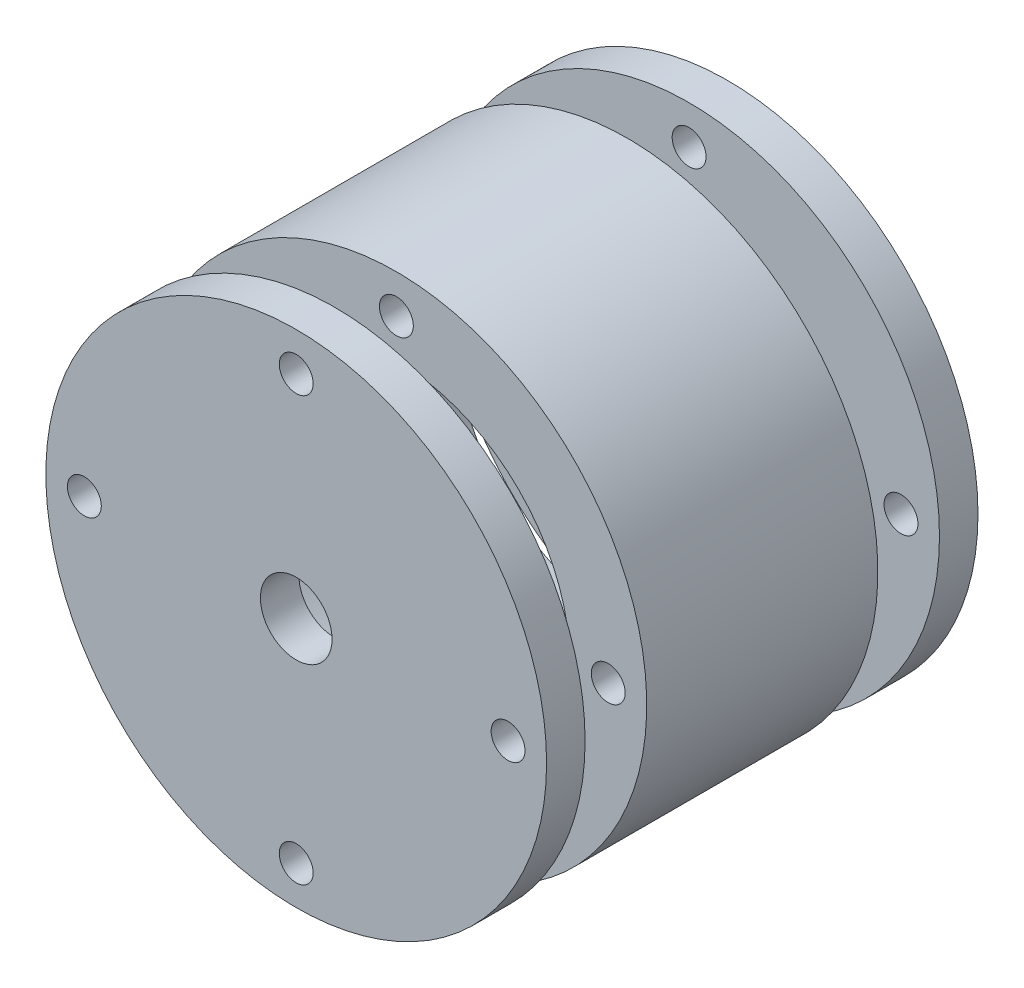
SolidWorks part; units mm, degrees
ref_plane "Front Plane" through (0, 0, 0) normal (0, 0, 1) x (1, 0, 0)
ref_plane "Top Plane" through (0, 0, 0) normal (0, 1, 0) x (1, 0, 0)
ref_plane "Right Plane" through (0, 0, 0) normal (1, 0, 0) x (0, 0, -1)
sketch "Sketch1" plane through (0, 0, 0) normal (0, 0, 1) x (1, 0, 0)
  line L0 (-32.9906, -34.2) -> (98.1862, -34.2)
  circle A0 centre (-32.9906, -34.2) radius 6.575 construction
  circle A1 centre (-32.9906, -34.2) radius 6.575
  circle A2 centre (-32.9906, -34.2) radius 8.875 construction
  circle A3 centre (-32.9906, -34.2) radius 8.875
sketch "Sketch2" plane through (0, 0, 0) normal (0, 0, 1) x (1, 0, 0)
  line L2 (-58.7906, -34.2) -> (-88.2906, -34.2)
  line L3 (-88.2906, -85) -> (-88.2906, 85) construction
  line L4 (88.2906, -34.2) -> (65.9936, -34.2)
  line L5 (-32.9906, -34.2) -> (98.1862, -34.2) construction
  line L6 (88.2906, 85) -> (88.2906, -85) construction
  circle A1 centre (33.4966, -33.7548) radius 4.65 construction
  circle A2 centre (33.4966, -33.7548) radius 4.65
  circle A3 centre (33.4966, -33.7548) radius 32.5
  circle A5 centre (33.4966, -33.7548) radius 27.5
  circle A6 centre (33.4966, -6.2548) radius 2.2
  circle A7 centre (5.9966, -33.7548) radius 2.2
  circle A8 centre (33.4966, -61.2548) radius 2.2
  circle A9 centre (60.9966, -33.7548) radius 2.2
  circle M40 centre (33.4966, -33.7548) radius 20.6
  circle M41 centre (33.4966, -6.2548) radius 2.2
  circle M42 centre (60.9966, -33.7548) radius 2.2
  circle M43 centre (33.4966, -61.2548) radius 2.2
  circle M44 centre (5.9966, -33.7548) radius 2.2
  dimension "D2" = 55
  dimension "D4" = 4.4
  dimension "D3" = 65
  dimension "D1" = 29.5
extrude "Boss-Extrude1" add sketch "Sketch2" along normal blind 5 contours A3 A2 | A3 A9 A5 A8 A7 A6 | A5 M42 M41 M44 M43 M40
sketch "Sketch3" plane through (0, 0, 0) normal (0, 0, -1) x (-1, 0, 0)
  line L0 (-5.9966, -33.7548) -> (-0.9966, -33.7548)
  line L1 (-5.9966, -33.7548) -> (-10.9966, -33.7548)
  circle A0 centre (-33.4966, -33.7548) radius 22.5
  circle A1 centre (-33.4966, -33.7548) radius 32.5
  circle A3 centre (-33.4966, -6.2548) radius 2.2
  circle A5 centre (-5.9966, -33.7548) radius 2.2
  circle A7 centre (-33.4966, -61.2548) radius 2.2
  circle A9 centre (-60.9966, -33.7548) radius 2.2
  circle A17 centre (-33.4966, -33.7548) radius 32.5
  circle A18 centre (-33.4966, -6.2548) radius 2.2
  circle A19 centre (-5.9966, -33.7548) radius 2.2
  circle A20 centre (-33.4966, -61.2548) radius 2.2
  circle A21 centre (-60.9966, -33.7548) radius 2.2
  dimension "D1" = 0
  dimension "D2" = 0
  dimension "D3" = 0
  dimension "D4" = 0
  dimension "D5" = 0
extrude "Boss-Extrude2" add sketch "Sketch3" along normal blind 30 from offset 8 separate body
ref_plane "Plane1" through (0, 0, -23) normal (0, 0, -1) x (-1, 0, 0)
mirror "Mirror1" about plane through (0, 0, -23) normal (0, 0, -1) of bodies 101
sketch "Sketch4" plane through (0, 0, 0) normal (0, 0, -1) x (-1, 0, 0)
  circle A0 centre (-33.4966, -33.7548) radius 4.65 construction
  circle A1 centre (-33.4966, -33.7548) radius 4.65
  circle A2 centre (-33.4966, -33.7548) radius 15.6
  circle A3 centre (-33.4966, -33.7548) radius 20.6
  dimension "D1" = 41.2
  dimension "D2" = 31.2
extrude "Cut-Extrude1" cut sketch "Sketch4" against normal blind 2.5 and the other way offset from surface (8 mm away) 2.5 contours A3 A2
sketch "Sketch5" plane through (0, 0, -46) normal (0, 0, 1) x (1, 0, 0)
  circle A0 centre (33.4966, -33.7548) radius 20.6 construction
  circle A1 centre (33.4966, -33.7548) radius 15.6 construction
  circle A2 centre (33.4966, -33.7548) radius 20.6
  circle A3 centre (33.4966, -33.7548) radius 15.6
extrude "Cut-Extrude2" cut sketch "Sketch5" against normal blind 2.5
equation "\"D2@Sketch2\"=\"D3@Sketch2\"-10"
